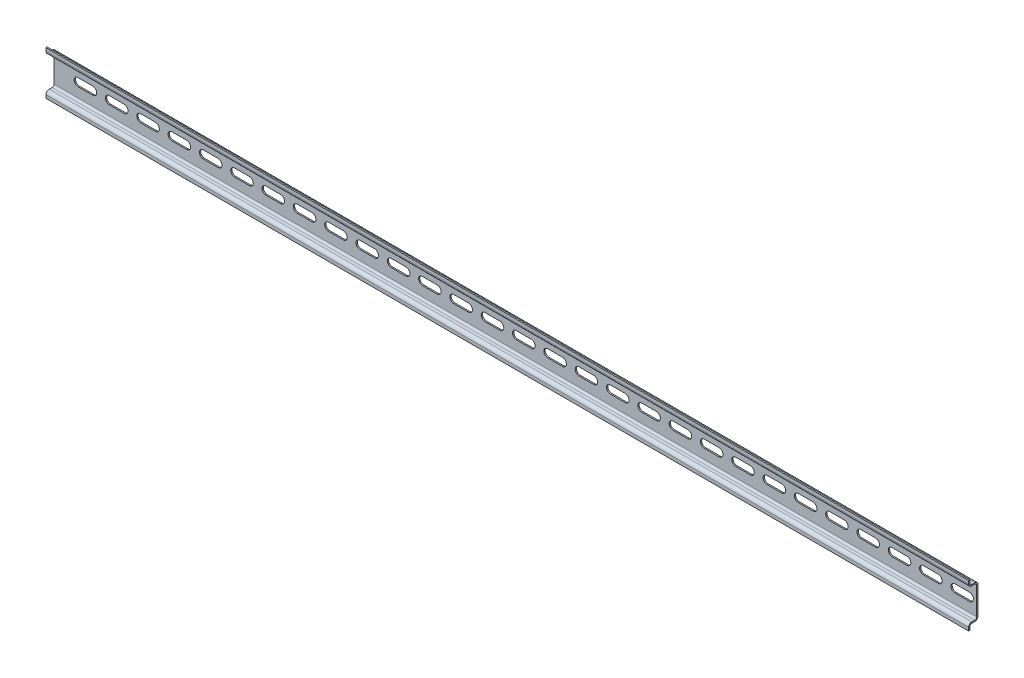
SolidWorks part; units mm, degrees
ref_plane "Front Plane" through (0, 0, 0) normal (0, 0, 1) x (1, 0, 0)
ref_plane "Top Plane" through (0, 0, 0) normal (0, 1, 0) x (1, 0, 0)
ref_plane "Right Plane" through (0, 0, 0) normal (1, 0, 0) x (0, 0, -1)
sketch "Sketch1" plane through (0, 0, 0) normal (1, 0, 0) x (0, 0, -1)
  line L0 (0, 0) -> (96.2341, 0) construction
  line L1 (0, 12.446) -> (0, -12.446)
  line L2 (0, -12.446) -> (-6.484, -12.446)
  line L3 (-6.484, -12.446) -> (-6.484, -17.526)
  line L4 (-6.484, -17.526) -> (-5.484, -17.526)
  line L5 (-5.484, -17.526) -> (-5.484, -13.462)
  line L6 (-5.484, -13.462) -> (1.016, -13.462)
  line L9 (1.016, -13.462) -> (1.016, 13.462)
  line L10 (-5.484, 17.526) -> (-5.484, 13.462)
  line L11 (-6.484, 17.526) -> (-5.484, 17.526)
  line L12 (-6.484, 12.446) -> (-6.484, 17.526)
  line L13 (0, 12.446) -> (-6.484, 12.446)
  line L14 (-5.484, 13.462) -> (1.016, 13.462)
  point P20 (1.016, 0)
  dimension "D1" = 96.2341
  dimension "D2" = 26.924
  dimension "D3" = 7.5
  dimension "D4" = 1
  dimension "D5" = 1.016
  dimension "D8" = 1.016
  dimension "D9" = 35.052
extrude "Boss-Extrude1" add sketch "Sketch1" along normal blind 1000
sketch "Sketch2" plane through (0, 0, -1.016) normal (0, 0, -1) x (-1, 0, 0)
  line L0 (-980.825, 0) -> (-969.175, 0) construction
  line L1 (-980.825, 3.175) -> (-969.175, 3.175)
  line L2 (-980.825, -3.175) -> (-969.175, -3.175)
  line L3 (-1000, -13.462) -> (-1000, 13.462) construction
  line L4 (-955.825, 0) -> (-944.175, 0) construction
  line L5 (-955.825, 3.175) -> (-944.175, 3.175)
  line L6 (-955.825, -3.175) -> (-944.175, -3.175)
  line L7 (-930.825, 0) -> (-919.175, 0) construction
  line L8 (-930.825, 3.175) -> (-919.175, 3.175)
  line L9 (-930.825, -3.175) -> (-919.175, -3.175)
  line L10 (-905.825, 0) -> (-894.175, 0) construction
  line L11 (-905.825, 3.175) -> (-894.175, 3.175)
  line L12 (-905.825, -3.175) -> (-894.175, -3.175)
  line L13 (-880.825, 0) -> (-869.175, 0) construction
  line L14 (-880.825, 3.175) -> (-869.175, 3.175)
  line L15 (-880.825, -3.175) -> (-869.175, -3.175)
  line L16 (-855.825, 0) -> (-844.175, 0) construction
  line L17 (-855.825, 3.175) -> (-844.175, 3.175)
  line L18 (-855.825, -3.175) -> (-844.175, -3.175)
  line L19 (-830.825, 0) -> (-819.175, 0) construction
  line L20 (-830.825, 3.175) -> (-819.175, 3.175)
  line L21 (-830.825, -3.175) -> (-819.175, -3.175)
  line L22 (-805.825, 0) -> (-794.175, 0) construction
  line L23 (-805.825, 3.175) -> (-794.175, 3.175)
  line L24 (-805.825, -3.175) -> (-794.175, -3.175)
  line L25 (-780.825, 0) -> (-769.175, 0) construction
  line L26 (-780.825, 3.175) -> (-769.175, 3.175)
  line L27 (-780.825, -3.175) -> (-769.175, -3.175)
  line L28 (-755.825, 0) -> (-744.175, 0) construction
  line L29 (-755.825, 3.175) -> (-744.175, 3.175)
  line L30 (-755.825, -3.175) -> (-744.175, -3.175)
  line L31 (-730.825, 0) -> (-719.175, 0) construction
  line L32 (-730.825, 3.175) -> (-719.175, 3.175)
  line L33 (-730.825, -3.175) -> (-719.175, -3.175)
  line L34 (-705.825, 0) -> (-694.175, 0) construction
  line L35 (-705.825, 3.175) -> (-694.175, 3.175)
  line L36 (-705.825, -3.175) -> (-694.175, -3.175)
  line L37 (-680.825, 0) -> (-669.175, 0) construction
  line L38 (-680.825, 3.175) -> (-669.175, 3.175)
  line L39 (-680.825, -3.175) -> (-669.175, -3.175)
  line L40 (-655.825, 0) -> (-644.175, 0) construction
  line L41 (-655.825, 3.175) -> (-644.175, 3.175)
  line L42 (-655.825, -3.175) -> (-644.175, -3.175)
  line L44 (-630.825, 0) -> (-619.175, 0) construction
  line L45 (-630.825, 3.175) -> (-619.175, 3.175)
  line L46 (-630.825, -3.175) -> (-619.175, -3.175)
  line L47 (-605.825, 0) -> (-594.175, 0) construction
  line L48 (-605.825, 3.175) -> (-594.175, 3.175)
  line L49 (-605.825, -3.175) -> (-594.175, -3.175)
  line L50 (-580.825, 0) -> (-569.175, 0) construction
  line L51 (-580.825, 3.175) -> (-569.175, 3.175)
  line L52 (-580.825, -3.175) -> (-569.175, -3.175)
  line L53 (-555.825, 0) -> (-544.175, 0) construction
  line L54 (-555.825, 3.175) -> (-544.175, 3.175)
  line L55 (-555.825, -3.175) -> (-544.175, -3.175)
  line L56 (-530.825, 0) -> (-519.175, 0) construction
  line L57 (-530.825, 3.175) -> (-519.175, 3.175)
  line L58 (-530.825, -3.175) -> (-519.175, -3.175)
  line L59 (-505.825, 0) -> (-494.175, 0) construction
  line L60 (-505.825, 3.175) -> (-494.175, 3.175)
  line L61 (-505.825, -3.175) -> (-494.175, -3.175)
  line L62 (-480.825, 0) -> (-469.175, 0) construction
  line L63 (-480.825, 3.175) -> (-469.175, 3.175)
  line L64 (-480.825, -3.175) -> (-469.175, -3.175)
  line L65 (-455.825, 0) -> (-444.175, 0) construction
  line L66 (-455.825, 3.175) -> (-444.175, 3.175)
  line L67 (-455.825, -3.175) -> (-444.175, -3.175)
  line L68 (-430.825, 0) -> (-419.175, 0) construction
  line L69 (-430.825, 3.175) -> (-419.175, 3.175)
  line L70 (-430.825, -3.175) -> (-419.175, -3.175)
  line L71 (-405.825, 0) -> (-394.175, 0) construction
  line L72 (-405.825, 3.175) -> (-394.175, 3.175)
  line L73 (-405.825, -3.175) -> (-394.175, -3.175)
  line L74 (-380.825, 0) -> (-369.175, 0) construction
  line L75 (-380.825, 3.175) -> (-369.175, 3.175)
  line L76 (-380.825, -3.175) -> (-369.175, -3.175)
  line L77 (-355.825, 0) -> (-344.175, 0) construction
  line L78 (-355.825, 3.175) -> (-344.175, 3.175)
  line L79 (-355.825, -3.175) -> (-344.175, -3.175)
  line L80 (-330.825, 0) -> (-319.175, 0) construction
  line L81 (-330.825, 3.175) -> (-319.175, 3.175)
  line L82 (-330.825, -3.175) -> (-319.175, -3.175)
  line L83 (-305.825, 0) -> (-294.175, 0) construction
  line L84 (-305.825, 3.175) -> (-294.175, 3.175)
  line L85 (-305.825, -3.175) -> (-294.175, -3.175)
  line L86 (-280.825, 0) -> (-269.175, 0) construction
  line L87 (-280.825, 3.175) -> (-269.175, 3.175)
  line L88 (-280.825, -3.175) -> (-269.175, -3.175)
  line L89 (-255.825, 0) -> (-244.175, 0) construction
  line L90 (-255.825, 3.175) -> (-244.175, 3.175)
  line L91 (-255.825, -3.175) -> (-244.175, -3.175)
  line L92 (-230.825, 0) -> (-219.175, 0) construction
  line L93 (-230.825, 3.175) -> (-219.175, 3.175)
  line L94 (-230.825, -3.175) -> (-219.175, -3.175)
  line L95 (-205.825, 0) -> (-194.175, 0) construction
  line L96 (-205.825, 3.175) -> (-194.175, 3.175)
  line L97 (-205.825, -3.175) -> (-194.175, -3.175)
  line L98 (-180.825, 0) -> (-169.175, 0) construction
  line L99 (-180.825, 3.175) -> (-169.175, 3.175)
  line L100 (-180.825, -3.175) -> (-169.175, -3.175)
  line L101 (-155.825, 0) -> (-144.175, 0) construction
  line L102 (-155.825, 3.175) -> (-144.175, 3.175)
  line L103 (-155.825, -3.175) -> (-144.175, -3.175)
  line L104 (-130.825, 0) -> (-119.175, 0) construction
  line L105 (-130.825, 3.175) -> (-119.175, 3.175)
  line L106 (-130.825, -3.175) -> (-119.175, -3.175)
  line L107 (-105.825, 0) -> (-94.175, 0) construction
  line L108 (-105.825, 3.175) -> (-94.175, 3.175)
  line L109 (-105.825, -3.175) -> (-94.175, -3.175)
  line L110 (-80.825, 0) -> (-69.175, 0) construction
  line L111 (-80.825, 3.175) -> (-69.175, 3.175)
  line L112 (-80.825, -3.175) -> (-69.175, -3.175)
  line L113 (-55.825, 0) -> (-44.175, 0) construction
  line L114 (-55.825, 3.175) -> (-44.175, 3.175)
  line L115 (-55.825, -3.175) -> (-44.175, -3.175)
  line L116 (-30.825, 0) -> (-19.175, 0) construction
  line L117 (-30.825, 3.175) -> (-19.175, 3.175)
  line L118 (-30.825, -3.175) -> (-19.175, -3.175)
  arc A0 (-980.825, 3.175) -> (-980.825, -3.175) centre (-980.825, 0) ccw
  arc A1 (-969.175, -3.175) -> (-969.175, 3.175) centre (-969.175, 0) ccw
  arc A2 (-955.825, 3.175) -> (-955.825, -3.175) centre (-955.825, 0) ccw
  arc A3 (-944.175, -3.175) -> (-944.175, 3.175) centre (-944.175, 0) ccw
  arc A4 (-930.825, 3.175) -> (-930.825, -3.175) centre (-930.825, 0) ccw
  arc A5 (-919.175, -3.175) -> (-919.175, 3.175) centre (-919.175, 0) ccw
  arc A6 (-905.825, 3.175) -> (-905.825, -3.175) centre (-905.825, 0) ccw
  arc A7 (-894.175, -3.175) -> (-894.175, 3.175) centre (-894.175, 0) ccw
  arc A8 (-880.825, 3.175) -> (-880.825, -3.175) centre (-880.825, 0) ccw
  arc A9 (-869.175, -3.175) -> (-869.175, 3.175) centre (-869.175, 0) ccw
  arc A10 (-855.825, 3.175) -> (-855.825, -3.175) centre (-855.825, 0) ccw
  arc A11 (-844.175, -3.175) -> (-844.175, 3.175) centre (-844.175, 0) ccw
  arc A12 (-830.825, 3.175) -> (-830.825, -3.175) centre (-830.825, 0) ccw
  arc A13 (-819.175, -3.175) -> (-819.175, 3.175) centre (-819.175, 0) ccw
  arc A14 (-805.825, 3.175) -> (-805.825, -3.175) centre (-805.825, 0) ccw
  arc A15 (-794.175, -3.175) -> (-794.175, 3.175) centre (-794.175, 0) ccw
  arc A16 (-780.825, 3.175) -> (-780.825, -3.175) centre (-780.825, 0) ccw
  arc A17 (-769.175, -3.175) -> (-769.175, 3.175) centre (-769.175, 0) ccw
  arc A18 (-755.825, 3.175) -> (-755.825, -3.175) centre (-755.825, 0) ccw
  arc A19 (-744.175, -3.175) -> (-744.175, 3.175) centre (-744.175, 0) ccw
  arc A20 (-730.825, 3.175) -> (-730.825, -3.175) centre (-730.825, 0) ccw
  arc A21 (-719.175, -3.175) -> (-719.175, 3.175) centre (-719.175, 0) ccw
  arc A22 (-705.825, 3.175) -> (-705.825, -3.175) centre (-705.825, 0) ccw
  arc A23 (-694.175, -3.175) -> (-694.175, 3.175) centre (-694.175, 0) ccw
  arc A24 (-680.825, 3.175) -> (-680.825, -3.175) centre (-680.825, 0) ccw
  arc A25 (-669.175, -3.175) -> (-669.175, 3.175) centre (-669.175, 0) ccw
  arc A26 (-655.825, 3.175) -> (-655.825, -3.175) centre (-655.825, 0) ccw
  arc A27 (-644.175, -3.175) -> (-644.175, 3.175) centre (-644.175, 0) ccw
  arc A28 (-630.825, 3.175) -> (-630.825, -3.175) centre (-630.825, 0) ccw
  arc A29 (-619.175, -3.175) -> (-619.175, 3.175) centre (-619.175, 0) ccw
  arc A30 (-605.825, 3.175) -> (-605.825, -3.175) centre (-605.825, 0) ccw
  arc A31 (-594.175, -3.175) -> (-594.175, 3.175) centre (-594.175, 0) ccw
  arc A32 (-580.825, 3.175) -> (-580.825, -3.175) centre (-580.825, 0) ccw
  arc A33 (-569.175, -3.175) -> (-569.175, 3.175) centre (-569.175, 0) ccw
  arc A34 (-555.825, 3.175) -> (-555.825, -3.175) centre (-555.825, 0) ccw
  arc A35 (-544.175, -3.175) -> (-544.175, 3.175) centre (-544.175, 0) ccw
  arc A36 (-530.825, 3.175) -> (-530.825, -3.175) centre (-530.825, 0) ccw
  arc A37 (-519.175, -3.175) -> (-519.175, 3.175) centre (-519.175, 0) ccw
  arc A38 (-505.825, 3.175) -> (-505.825, -3.175) centre (-505.825, 0) ccw
  arc A39 (-494.175, -3.175) -> (-494.175, 3.175) centre (-494.175, 0) ccw
  arc A40 (-480.825, 3.175) -> (-480.825, -3.175) centre (-480.825, 0) ccw
  arc A41 (-469.175, -3.175) -> (-469.175, 3.175) centre (-469.175, 0) ccw
  arc A42 (-455.825, 3.175) -> (-455.825, -3.175) centre (-455.825, 0) ccw
  arc A43 (-444.175, -3.175) -> (-444.175, 3.175) centre (-444.175, 0) ccw
  arc A44 (-430.825, 3.175) -> (-430.825, -3.175) centre (-430.825, 0) ccw
  arc A45 (-419.175, -3.175) -> (-419.175, 3.175) centre (-419.175, 0) ccw
  arc A46 (-405.825, 3.175) -> (-405.825, -3.175) centre (-405.825, 0) ccw
  arc A47 (-394.175, -3.175) -> (-394.175, 3.175) centre (-394.175, 0) ccw
  arc A48 (-380.825, 3.175) -> (-380.825, -3.175) centre (-380.825, 0) ccw
  arc A49 (-369.175, -3.175) -> (-369.175, 3.175) centre (-369.175, 0) ccw
  arc A50 (-355.825, 3.175) -> (-355.825, -3.175) centre (-355.825, 0) ccw
  arc A51 (-344.175, -3.175) -> (-344.175, 3.175) centre (-344.175, 0) ccw
  arc A52 (-330.825, 3.175) -> (-330.825, -3.175) centre (-330.825, 0) ccw
  arc A53 (-319.175, -3.175) -> (-319.175, 3.175) centre (-319.175, 0) ccw
  arc A54 (-305.825, 3.175) -> (-305.825, -3.175) centre (-305.825, 0) ccw
  arc A55 (-294.175, -3.175) -> (-294.175, 3.175) centre (-294.175, 0) ccw
  arc A56 (-280.825, 3.175) -> (-280.825, -3.175) centre (-280.825, 0) ccw
  arc A57 (-269.175, -3.175) -> (-269.175, 3.175) centre (-269.175, 0) ccw
  arc A58 (-255.825, 3.175) -> (-255.825, -3.175) centre (-255.825, 0) ccw
  arc A59 (-244.175, -3.175) -> (-244.175, 3.175) centre (-244.175, 0) ccw
  arc A60 (-230.825, 3.175) -> (-230.825, -3.175) centre (-230.825, 0) ccw
  arc A61 (-219.175, -3.175) -> (-219.175, 3.175) centre (-219.175, 0) ccw
  arc A62 (-205.825, 3.175) -> (-205.825, -3.175) centre (-205.825, 0) ccw
  arc A63 (-194.175, -3.175) -> (-194.175, 3.175) centre (-194.175, 0) ccw
  arc A64 (-180.825, 3.175) -> (-180.825, -3.175) centre (-180.825, 0) ccw
  arc A65 (-169.175, -3.175) -> (-169.175, 3.175) centre (-169.175, 0) ccw
  arc A66 (-155.825, 3.175) -> (-155.825, -3.175) centre (-155.825, 0) ccw
  arc A67 (-144.175, -3.175) -> (-144.175, 3.175) centre (-144.175, 0) ccw
  arc A68 (-130.825, 3.175) -> (-130.825, -3.175) centre (-130.825, 0) ccw
  arc A69 (-119.175, -3.175) -> (-119.175, 3.175) centre (-119.175, 0) ccw
  arc A70 (-105.825, 3.175) -> (-105.825, -3.175) centre (-105.825, 0) ccw
  arc A71 (-94.175, -3.175) -> (-94.175, 3.175) centre (-94.175, 0) ccw
  arc A72 (-80.825, 3.175) -> (-80.825, -3.175) centre (-80.825, 0) ccw
  arc A73 (-69.175, -3.175) -> (-69.175, 3.175) centre (-69.175, 0) ccw
  arc A74 (-55.825, 3.175) -> (-55.825, -3.175) centre (-55.825, 0) ccw
  arc A75 (-44.175, -3.175) -> (-44.175, 3.175) centre (-44.175, 0) ccw
  arc A76 (-30.825, 3.175) -> (-30.825, -3.175) centre (-30.825, 0) ccw
  arc A77 (-19.175, -3.175) -> (-19.175, 3.175) centre (-19.175, 0) ccw
  point P3 (-975, 0)
  point P8 (-984, 0)
  point P9 (-966, 0)
  point P15 (-950, 0)
  point P22 (-925, 0)
  point P29 (-900, 0)
  point P36 (-875, 0)
  point P43 (-850, 0)
  point P50 (-825, 0)
  point P57 (-800, 0)
  point P64 (-775, 0)
  point P71 (-750, 0)
  point P78 (-725, 0)
  point P85 (-700, 0)
  point P92 (-675, 0)
  point P99 (-650, 0)
  point P107 (-625, 0)
  point P114 (-600, 0)
  point P121 (-575, 0)
  point P128 (-550, 0)
  point P135 (-525, 0)
  point P142 (-500, 0)
  point P149 (-475, 0)
  point P156 (-450, 0)
  point P163 (-425, 0)
  point P170 (-400, 0)
  point P177 (-375, 0)
  point P184 (-350, 0)
  point P191 (-325, 0)
  point P198 (-300, 0)
  point P205 (-275, 0)
  point P212 (-250, 0)
  point P219 (-225, 0)
  point P226 (-200, 0)
  point P233 (-175, 0)
  point P240 (-150, 0)
  point P247 (-125, 0)
  point P254 (-100, 0)
  point P261 (-75, 0)
  point P268 (-50, 0)
  point P274 (-25, 0)
  dimension "D1" = 3.175
  dimension "D2" = 18
  dimension "D3" = 25
  dimension "D4" = 39
extrude "Cut-Extrude1" cut sketch "Sketch2" against normal through all
fillet "Fillet1" radius 2.54 4 edges at (500, -12.446, 6.484) (500, 12.446, 6.484) (500, -13.462, -1.016) (500, 13.462, -1.016)
fillet "Fillet2" radius 1.524 4 edges at (500, -13.462, 5.484) (500, 12.446, 0) (500, -12.446, 0) (500, 13.462, 5.484)
sketch "Sketch3" plane through (0, 0, -1.016) normal (0, 0, -1) x (-1, 0, 0)
  line L0 (-1000, -17.526) -> (0, -17.526) construction
  line L1 (-1000, 17.526) -> (-736.6, 17.526)
  line L2 (-1000, 17.526) -> (-1000, -17.526)
  line L3 (-1000, -17.526) -> (-736.6, -17.526)
  line L4 (-736.6, 17.526) -> (-736.6, -17.526)
  line L5 (0, -10.922) -> (0, 10.922) construction
  dimension "D1" = 736.6
extrude "Cut-Extrude2" cut sketch "Sketch3" against normal through all both and the other way through all
